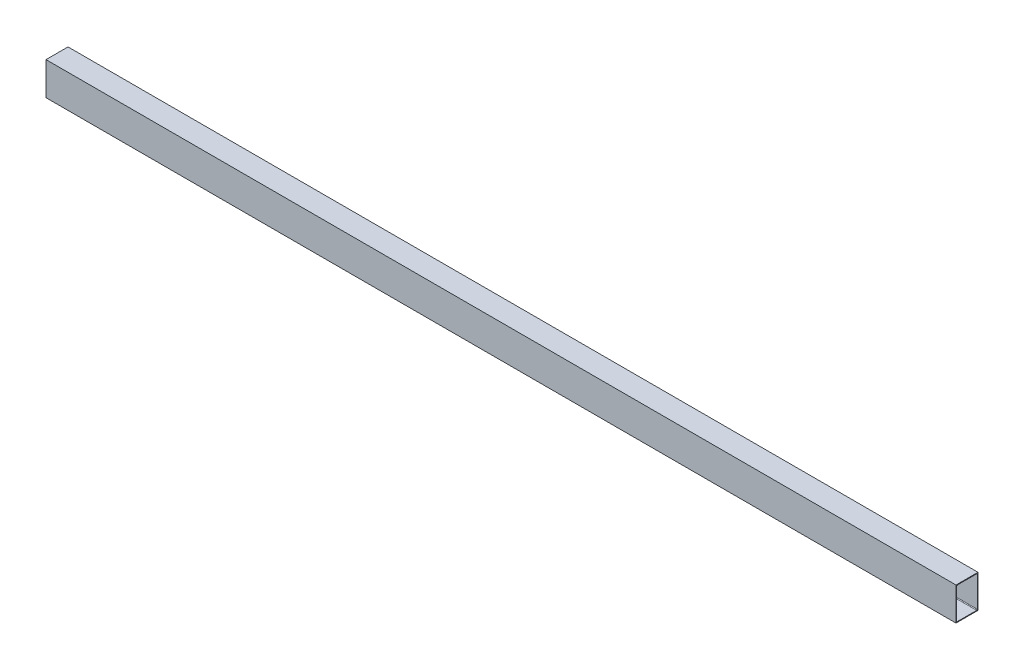
SolidWorks part; units mm, degrees
material "ASTM A500 Grade B Steel"
ref_plane "Front Plane" through (0, 0, 0) normal (0, 0, 1) x (1, 0, 0)
ref_plane "Top Plane" through (0, 0, 0) normal (0, 1, 0) x (1, 0, 0)
ref_plane "Right Plane" through (0, 0, 0) normal (1, 0, 0) x (0, 0, -1)
sketch "Sketch1" plane through (0, 0, 0) normal (1, 0, 0) x (0, 0, -1)
  line L0 (-98.425, 6.35) -> (-98.425, 146.05)
  line L1 (0, 0) -> (-101.6, 0)
  line L2 (0, 0) -> (0, 152.4)
  line L3 (0, 152.4) -> (-101.6, 152.4)
  line L4 (-101.6, 0) -> (-101.6, 152.4)
  line L5 (-6.35, 149.225) -> (-95.25, 149.225)
  line L6 (-3.175, 6.35) -> (-3.175, 146.05)
  line L7 (-6.35, 3.175) -> (-95.25, 3.175)
  line L8 (-98.425, 3.175) -> (-98.425, 149.225) construction
  line L9 (-3.175, 3.175) -> (-98.425, 3.175) construction
  line L10 (-3.175, 3.175) -> (-3.175, 149.225) construction
  line L11 (-3.175, 149.225) -> (-98.425, 149.225) construction
  arc A0 (-98.425, 6.35) -> (-95.25, 3.175) centre (-95.25, 6.35) ccw
  arc A1 (-3.175, 6.35) -> (-6.35, 3.175) centre (-6.35, 6.35) cw
  arc A2 (-6.35, 149.225) -> (-3.175, 146.05) centre (-6.35, 146.05) cw
  arc A3 (-98.425, 146.05) -> (-95.25, 149.225) centre (-95.25, 146.05) cw
  dimension "D4" = 3.175
  dimension "D1" = 152.4
  dimension "D2" = 101.6
  dimension "D3" = 3.175
extrude "Boss-Extrude1" add sketch "Sketch1" along normal blind 4200
equation "\"D4@Sketch1\"=\"D3@Sketch1\""
